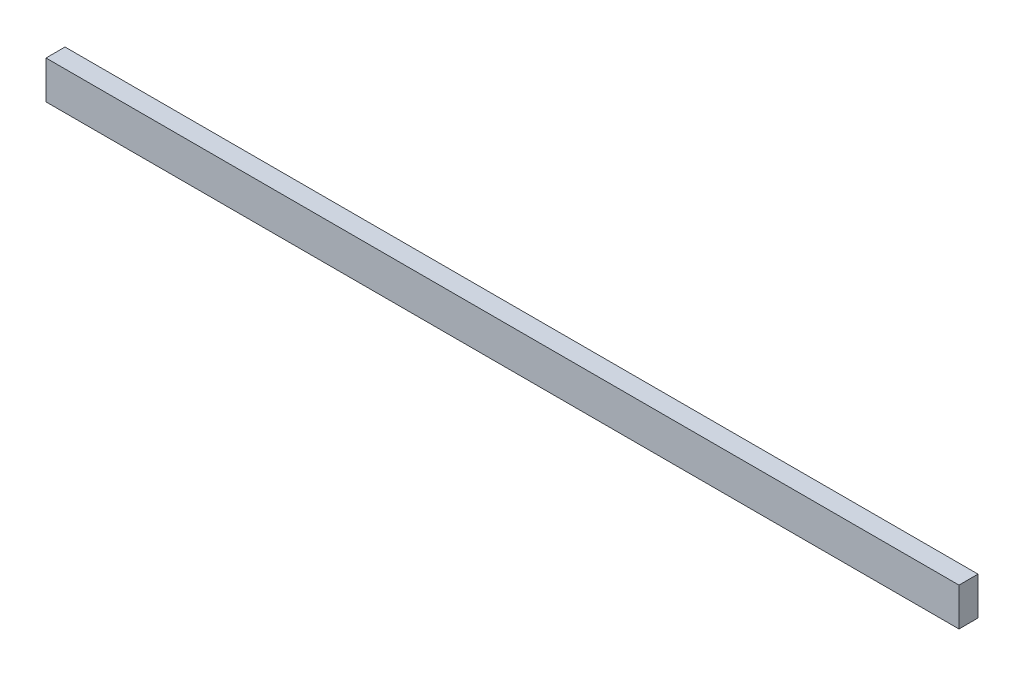
SolidWorks part; units mm, degrees
ref_plane "Front Plane" through (0, 0, 0) normal (0, 0, 1) x (1, 0, 0)
ref_plane "Top Plane" through (0, 0, 0) normal (0, 1, 0) x (1, 0, 0)
ref_plane "Right Plane" through (0, 0, 0) normal (1, 0, 0) x (0, 0, -1)
sketch "Sketch1" plane through (0, 0, 0) normal (0, 0, 1) x (1, 0, 0)
  line L1 (-1219.2, -50.8) -> (1219.2, -50.8)
  line L2 (-1219.2, -50.8) -> (-1219.2, 50.8)
  line L3 (-1219.2, 50.8) -> (1219.2, 50.8)
  line L4 (1219.2, -50.8) -> (1219.2, 50.8)
  line L5 (-1219.2, -50.8) -> (1219.2, 50.8) construction
  line L6 (-1219.2, 50.8) -> (1219.2, -50.8) construction
  point P0 (0, 0)
  dimension "D1" = 101.6
  dimension "D2" = 2438.4
extrude "Boss-Extrude1" add sketch "Sketch1" along normal blind 50.8
